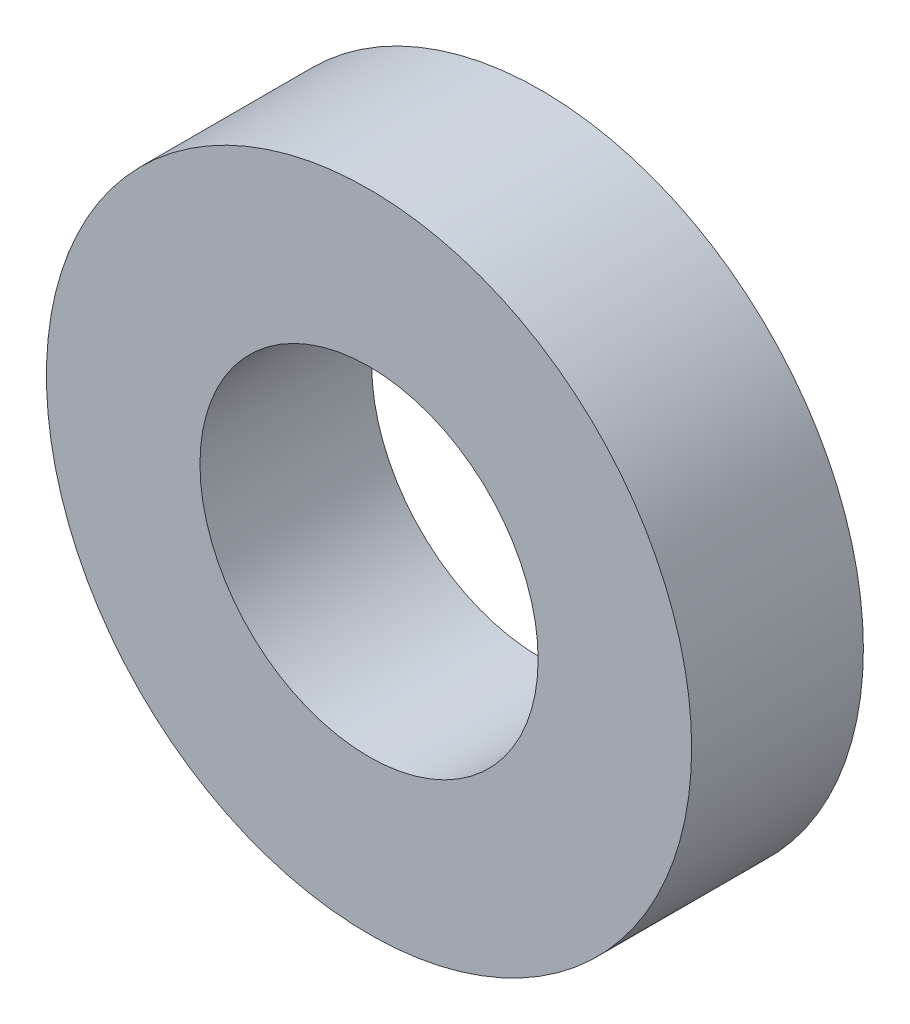
SolidWorks part; units mm, degrees
ref_plane "Plan de face" through (0, 0, 0) normal (1, 0, 0) x (0, 1, 0)
ref_plane "Plan de dessus" through (0, 0, 0) normal (0, 0, 1) x (0, 1, 0)
ref_plane "Plan de droite" through (0, 0, 0) normal (0, 1, 0) x (-1, 0, 0)
sketch "Esquisse1" plane through (0, 0, 0) normal (0, 0, 1) x (0, 1, 0)
  circle A0 centre (0, 0) radius 7.89
  circle A1 centre (0, 0) radius 4.135
  dimension "D1" = 8.27
  dimension "D2" = 15.78
extrude "Boss.-Extru.1" add sketch "Esquisse1" along normal blind 4.2
